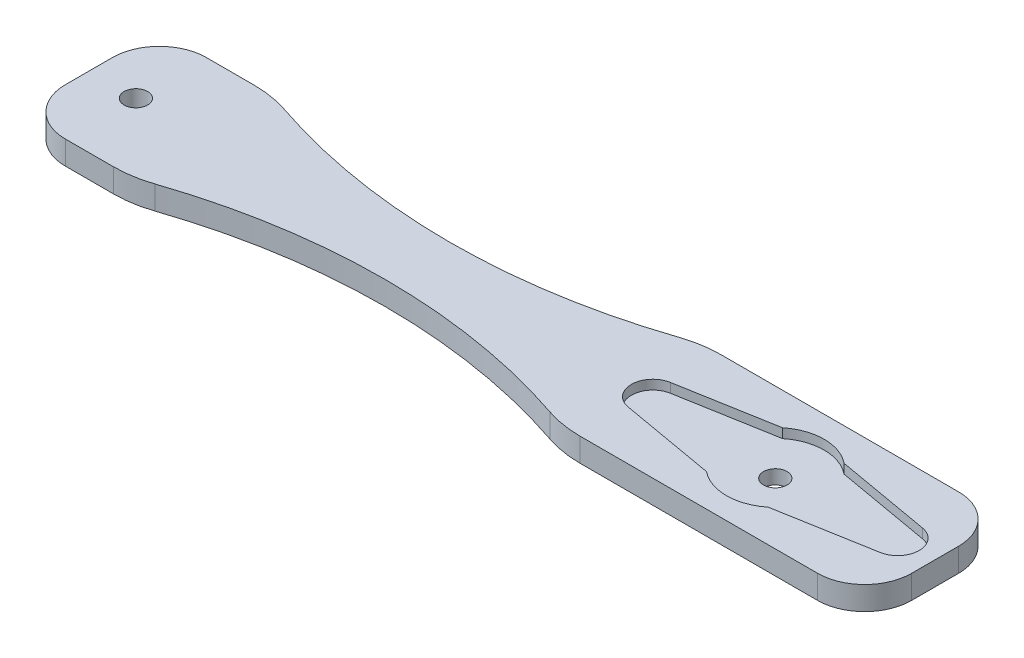
SolidWorks part; units mm, degrees
material "6061 Alloy"
ref_plane "Front Plane" through (0, 0, 0) normal (0, 0, 1) x (1, 0, 0)
ref_plane "Top Plane" through (0, 0, 0) normal (0, 1, 0) x (1, 0, 0)
ref_plane "Right Plane" through (0, 0, 0) normal (1, 0, 0) x (0, 0, -1)
sketch "Sketch1" plane through (0, 0, 0) normal (0, 1, 0) x (1, 0, 0)
  line L1 (6.35, 0) -> (107.95, 0)
  line L2 (0, 6.35) -> (0, 12.7)
  line L3 (6.35, 19.05) -> (107.95, 19.05)
  line L4 (114.3, 6.35) -> (114.3, 12.7)
  arc A0 (114.3, 6.35) -> (107.95, 0) centre (107.95, 6.35) cw
  arc A1 (114.3, 12.7) -> (107.95, 19.05) centre (107.95, 12.7) ccw
  arc A2 (6.35, 0) -> (0, 6.35) centre (6.35, 6.35) cw
  arc A3 (0, 12.7) -> (6.35, 19.05) centre (6.35, 12.7) cw
  point P7 (114.3, 0)
  point P12 (0, 0)
  point P15 (0, 19.05)
  dimension "D3" = 6.35
  dimension "D4" = 6.35
  dimension "D1" = 114.3
  dimension "D2" = 19.05
extrude "Boss-Extrude1" add sketch "Sketch1" along normal blind 3.175
sketch "Sketch4" plane through (0, 3.175, 0) normal (0, 1, 0) x (1, 0, 0)
  line L4 (109.7443, 12.3849) -> (96.8686, 14.6552)
  line L5 (75.6757, 12.3849) -> (88.5514, 14.6552)
  line L6 (75.6757, 6.6651) -> (88.5514, 4.3948)
  line L7 (109.7443, 6.6651) -> (96.8686, 4.3948)
  arc A4 (96.8686, 14.6552) -> (88.5514, 14.6552) centre (92.71, 9.525) ccw
  arc A5 (75.6757, 12.3849) -> (75.6757, 6.6651) centre (76.18, 9.525) ccw
  arc A6 (88.5514, 4.3948) -> (96.8686, 4.3948) centre (92.71, 9.525) ccw
  arc A7 (109.7443, 12.3849) -> (109.7443, 6.6651) centre (109.24, 9.525) cw
extrude "Cut-Extrude2" cut sketch "Sketch4" against normal blind 1.27
hole_wizard "1/8 (0.125) Diameter Hole1" positions "Sketch5" profile "Sketch6" hole size "1/8" standard "ANSI Inch" end condition through all
sketch "Sketch5" plane through (0, 3.175, 0) normal (0, 1, 0) x (1, 0, 0)
  line L0 (0, 12.7) -> (0, 6.35) construction
  point P0 (6.35, 9.525)
  dimension "D1" = 6.35
sketch "Sketch6" plane through (6.35, 3.175, -9.525) normal (1, 0, 0) x (0, 0, 1)
  line L0 (0, 0) -> (0, 3.175)
  line L1 (0, 3.175) -> (1.5875, 3.175)
  line L2 (1.5875, 3.175) -> (1.5875, 0)
  line L5 (1.5875, 0) -> (0, 0)
  line L11 (0, -6.35) -> (0, 107.95) construction
  dimension "Thru Hole Dia." = 3.175
  dimension "Thru Hole Depth" = 3.175
sketch "Sketch7" plane through (0, 3.175, 0) normal (0, 1, 0) x (1, 0, 0)
  line L0 (107.95, 19.05) -> (6.35, 19.05) construction
  line L1 (0, 9.525) -> (114.3, 9.525) construction
  line L2 (0, 12.7) -> (0, 6.35) construction
  line L3 (114.3, 6.35) -> (114.3, 12.7) construction
  line L4 (15.4153, 19.05) -> (73.276, 19.05)
  line L5 (73.276, 0) -> (15.4153, 0)
  arc A0 (15.4153, 19.05) -> (73.276, 19.05) centre (44.3456, 97.4109) ccw
  arc A1 (15.4153, 0) -> (73.276, 0) centre (44.3456, -78.3609) cw
extrude "Cut-Extrude3" cut sketch "Sketch7" against normal through all
fillet "Fillet1" radius 15 4 edges at (15.4153, 1.5875, 0) (73.276, 1.5875, 0) (73.276, 1.5875, -19.05) (15.4153, 1.5875, -19.05)
hole_wizard "1/8 (0.125) Diameter Hole2" positions "Sketch8" profile "Sketch9" hole size "1/8" standard "ANSI Inch" end condition through all
sketch "Sketch8" plane through (0, 3.175, 0) normal (0, 1, 0) x (1, 0, 0)
  point P0 (92.71, 9.525)
sketch "Sketch9" plane through (92.71, 3.175, -9.525) normal (1, 0, 0) x (0, 0, 1)
  line L0 (0, 0) -> (0, 3.175)
  line L1 (0, 3.175) -> (1.5875, 3.175)
  line L2 (1.5875, 3.175) -> (1.5875, 0)
  line L5 (1.5875, 0) -> (0, 0)
  line L11 (0, -6.35) -> (0, 107.95) construction
  dimension "Thru Hole Dia." = 3.175
  dimension "Thru Hole Depth" = 3.175
